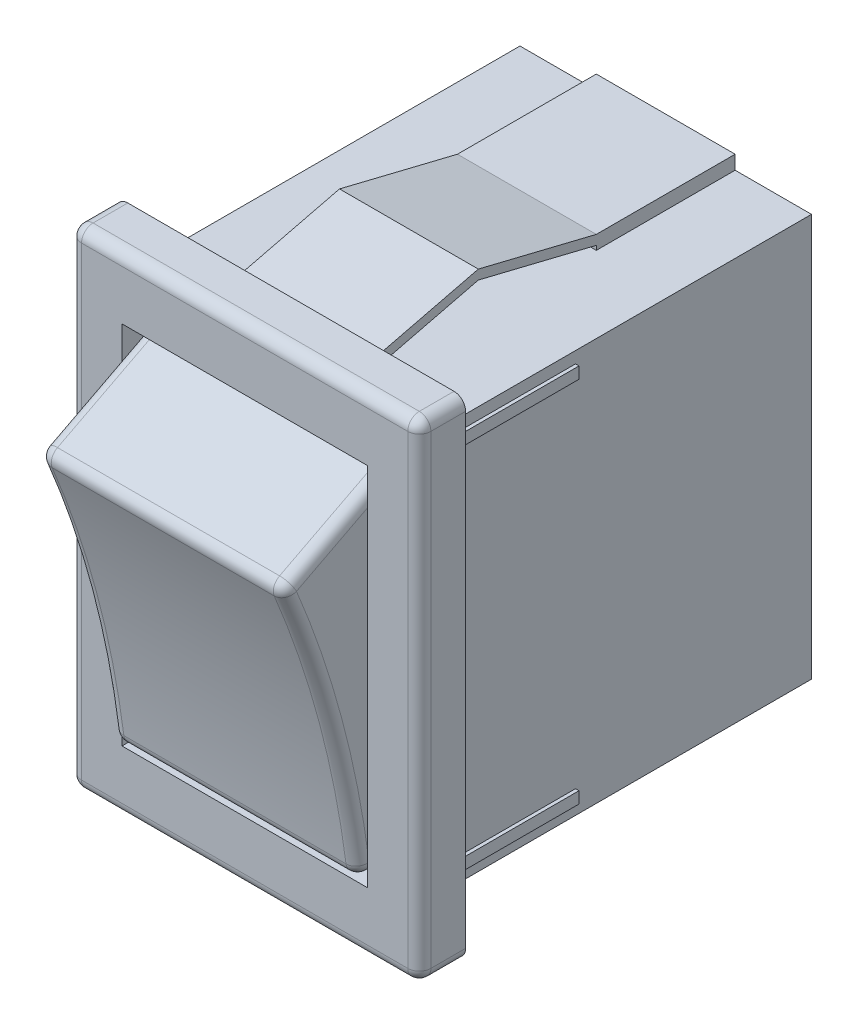
SolidWorks part; units mm, degrees
ref_plane "Front Plane" through (0, 0, 0) normal (0, 0, 1) x (1, 0, 0)
ref_plane "Top Plane" through (0, 0, 0) normal (0, 1, 0) x (1, 0, 0)
ref_plane "Right Plane" through (0, 0, 0) normal (1, 0, 0) x (0, 0, -1)
sketch "Sketch1" plane through (0, 0, 0) normal (0, 0, 1) x (1, 0, 0)
  line L1 (-7.55, -10.55) -> (7.55, -10.55)
  line L2 (-7.55, -10.55) -> (-7.55, 10.55)
  line L3 (-7.55, 10.55) -> (7.55, 10.55)
  line L4 (7.55, -10.55) -> (7.55, 10.55)
  line L5 (-7.55, -10.55) -> (7.55, 10.55) construction
  line L6 (-7.55, 10.55) -> (7.55, -10.55) construction
  line L7 (5.3, -7.9) -> (-5.3, -7.9)
  line L8 (5.3, -7.9) -> (5.3, 7.9)
  line L9 (5.3, 7.9) -> (-5.3, 7.9)
  line L10 (-5.3, -7.9) -> (-5.3, 7.9)
  line L11 (5.3, -7.9) -> (-5.3, 7.9) construction
  line L12 (5.3, 7.9) -> (-5.3, -7.9) construction
  point P0 (0, 0)
  point P6 (0, 0)
  point P11 (0, 0)
  dimension "D1" = 21.1
  dimension "D2" = 15.1
  dimension "D3" = 15.8
  dimension "D4" = 10.6
extrude "Boss-Extrude1" add sketch "Sketch1" along normal blind 2
fillet "Fillet2" radius 0.5 8 edges at (-7.55, -10.55, 1) (7.55, -10.55, 1) (-7.55, 10.55, 1) (7.55, 10.55, 1) (0, -10.55, 2) (-7.55, 0, 2) (0, 10.55, 2) (7.55, 0, 2)
sketch "Sketch2" plane through (0, 0, 0) normal (0, 0, -1) x (-1, 0, 0)
  line L1 (-6.3, -8.7) -> (6.3, -8.7)
  line L2 (-6.3, -8.7) -> (-6.3, 8.7)
  line L3 (-6.3, 8.7) -> (6.3, 8.7)
  line L4 (6.3, -8.7) -> (6.3, 8.7)
  line L5 (-6.3, -8.7) -> (6.3, 8.7) construction
  line L6 (-6.3, 8.7) -> (6.3, -8.7) construction
  point P0 (0, 0)
  dimension "D1" = 12.6
  dimension "D2" = 17.4
extrude "Boss-Extrude2" add sketch "Sketch2" along normal blind 16.2
sketch "Sketch3" plane through (0, 0, 0) normal (0, 0, -1) x (-1, 0, 0)
  line L0 (-6.3, 8.7) -> (-6.3, -8.7) construction
  line L1 (-6.3, 8.2) -> (-6.45, 8.2)
  line L2 (-6.3, 8.2) -> (-6.3, 7.7)
  line L3 (-6.3, 7.7) -> (-6.45, 7.7)
  line L4 (-6.45, 8.2) -> (-6.45, 7.7)
  line L5 (6.3, -8.7) -> (6.3, 8.7) construction
  line L6 (6.3, 8.2) -> (6.45, 8.2)
  line L7 (6.3, 8.2) -> (6.3, 7.7)
  line L8 (6.3, 7.7) -> (6.45, 7.7)
  line L9 (6.45, 8.2) -> (6.45, 7.7)
  line L10 (6.3, 8.7) -> (-6.3, 8.7) construction
  line L11 (0, 0) -> (6.3, 0) construction
  line L12 (6.45, -8.2) -> (6.45, -7.7)
  line L13 (6.3, -7.7) -> (6.45, -7.7)
  line L14 (6.3, -8.2) -> (6.3, -7.7)
  line L15 (6.3, -8.2) -> (6.45, -8.2)
  line L16 (-6.45, -8.2) -> (-6.45, -7.7)
  line L17 (-6.3, -7.7) -> (-6.45, -7.7)
  line L18 (-6.3, -8.2) -> (-6.3, -7.7)
  line L19 (-6.3, -8.2) -> (-6.45, -8.2)
  dimension "D1" = 12.9
  dimension "D2" = 0.5
  dimension "D3" = 0.5
extrude "Boss-Extrude3" add sketch "Sketch3" along normal blind 6
sketch "Sketch4" plane through (0, 0, 0) normal (1, 0, 0) x (0, 0, -1)
  line L0 (0, 0) -> (16.2, 0) construction
  line L1 (16.2, 8.7) -> (16.2, -8.7) construction
  line L2 (16.2, 8.7) -> (16.2, 9.3)
  line L3 (16.2, 9.3) -> (10.2, 9.3)
  line L4 (10.2, 9.3) -> (5.1, 10.55)
  line L5 (5.1, 10.55) -> (0, 9.3)
  line L6 (0, -10.05) -> (0, 10.05) construction
  line L7 (0, 9.3) -> (0, 8.8882)
  line L8 (0, 8.8882) -> (5.1, 10.1382)
  line L9 (5.1, 10.1382) -> (10.2, 8.8882)
  line L10 (10.2, 8.8882) -> (10.2, 8.7)
  line L11 (16.2, 8.7) -> (0, 8.7) construction
  line L12 (5.1, 10.55) -> (0, 10.55) construction
  line L13 (5.1, 10.1382) -> (5.1, 10.55) construction
  line L14 (10.2, 8.7) -> (16.2, 8.7)
  line L15 (5.1, -10.1382) -> (5.1, -10.55) construction
  line L16 (5.1, -10.55) -> (0, -10.55) construction
  line L17 (10.2, -8.7) -> (16.2, -8.7)
  line L18 (10.2, -8.8882) -> (10.2, -8.7)
  line L19 (5.1, -10.1382) -> (10.2, -8.8882)
  line L20 (0, -8.8882) -> (5.1, -10.1382)
  line L21 (0, -9.3) -> (0, -8.8882)
  line L22 (5.1, -10.55) -> (0, -9.3)
  line L23 (10.2, -9.3) -> (5.1, -10.55)
  line L24 (16.2, -9.3) -> (10.2, -9.3)
  line L25 (16.2, -8.7) -> (16.2, -9.3)
  dimension "D1" = 18.6
  dimension "D2" = 6
  dimension "D3" = 0.4
extrude "Boss-Extrude4" add sketch "Sketch4" along normal mid plane 6
sketch "Sketch5" plane through (0, 0, 0) normal (1, 0, 0) x (0, 0, -1)
  line L0 (0, 0) -> (16.2, 0) construction
  line L1 (0, -10.05) -> (0, 10.05) construction
  line L2 (16.2, 8.7) -> (16.2, -8.7) construction
  line L3 (0.75, 0) -> (-4.0306, -1.281) construction
  line L4 (-5.7, 4.9493) -> (-2.3612, -7.5112) construction
  line L5 (-5.289, 5.162) -> (0, 7.9)
  line L6 (-1.8989, -7.4899) -> (4.0505, -7.2166)
  line L7 (4.0505, -7.2166) -> (0, 7.9)
  line L8 (-2, -7.9) -> (0, -7.9) construction
  line L9 (-2, 7.9) -> (0, 7.9) construction
  arc A0 (-5.5205, 4.5254) -> (-2.4177, -7.0544) centre (-47.0485, -12.8076) cw
  arc A1 (-1.8989, -7.4899) -> (-2.4177, -7.0544) centre (-1.9218, -6.9905) cw
  arc A2 (-5.289, 5.162) -> (-5.5205, 4.5254) centre (-5.0591, 4.718) ccw
  point P10 (-4.0306, -1.281)
  dimension "D5" = 45
  dimension "D6" = 0.5
  dimension "D1" = 15
  dimension "D2" = 12.9
  dimension "D3" = 5.7
  dimension "D4" = 0.75
extrude "Boss-Extrude5" add sketch "Sketch5" along normal mid plane 10.6 separate body
fillet "Fillet3" radius 0.5 10 edges at (-5.3, 6.531, 2.6445) (-5.3, 4.8889, 5.529) (-5.3, -7.3533, -1.0758) (-5.3, -7.3734, 2.2433) (5.3, 6.531, 2.6445) (5.3, 4.8889, 5.529) (5.3, -7.3533, -1.0758) (5.3, -7.3734, 2.2433) (-5.3, -1.1607, 3.5818) (5.3, -1.1607, 3.5818)
